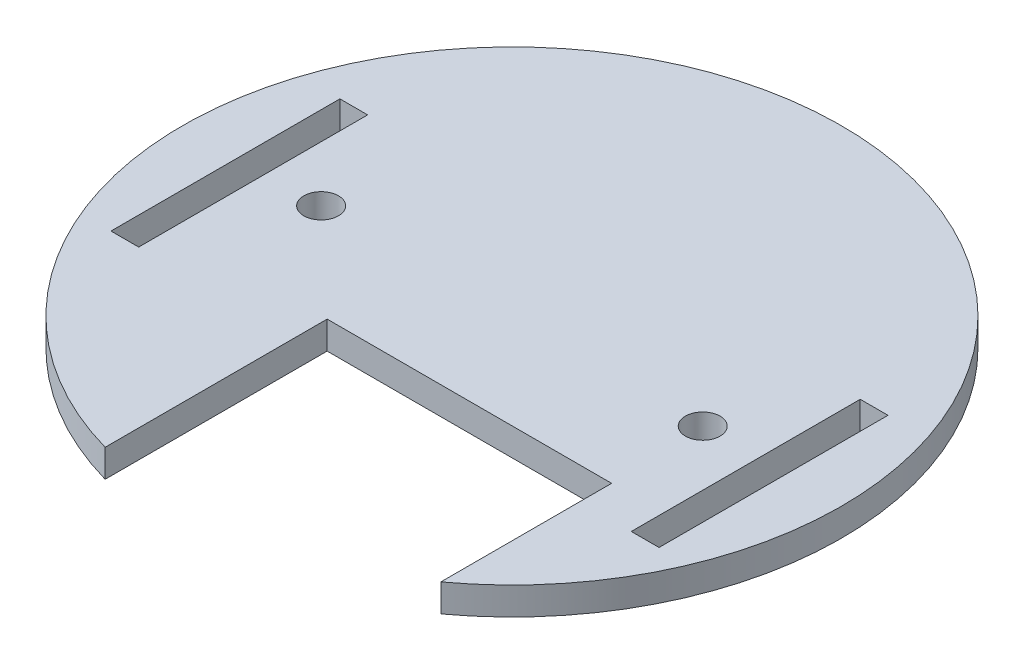
SolidWorks part; units mm, degrees
ref_plane "Front Plane" through (0, 0, 0) normal (0, 0, 1) x (1, 0, 0)
ref_plane "Top Plane" through (0, 0, 0) normal (0, 1, 0) x (1, 0, 0)
ref_plane "Right Plane" through (0, 0, 0) normal (1, 0, 0) x (0, 0, -1)
sketch "Sketch1" plane through (0, 0, 0) normal (0, 1, 0) x (1, 0, 0)
  line L0 (-47.5, 0) -> (47.5, 0) construction
  line L1 (0, 47.5) -> (0, -47.75) construction
  line L2 (-12.929, -45.7066) -> (-12.929, -13.7066)
  line L3 (-12.929, -13.7066) -> (28.071, -13.7066)
  line L4 (28.071, -13.7066) -> (28.071, -38.318)
  line L5 (35.5, -18.2987) -> (39.5, -18.2987)
  line L6 (-35.5, -18.2987) -> (-39.5, -18.2987)
  line L7 (-35.5, -18.2987) -> (-35.5, 9.1514)
  line L8 (-35.5, 9.1514) -> (-35.5, 14.7013)
  line L9 (-39.5, -18.2987) -> (-39.5, 14.7013)
  line L10 (35.5, 9.1514) -> (35.5, 14.7013)
  line L11 (39.5, -18.2987) -> (39.5, 14.7013)
  line L12 (35.5, -18.2987) -> (35.5, 9.1514)
  line L13 (35.5, 14.7013) -> (39.5, 14.7013)
  line L14 (-39.5, 14.7013) -> (-35.5, 14.7013)
  line L15 (-12.929, -42.8825) -> (-12.929, 45.7066) construction
  arc A0 (28.071, -38.318) -> (-12.929, -45.7066) centre (0, 0) ccw
  circle A1 centre (-27.5, 0) radius 2.5
  circle A2 centre (27.5, 0) radius 2.5
  dimension "D1" = 95
  dimension "D2" = 5
  dimension "D3" = 55
  dimension "D4" = 32
  dimension "D5" = 41
  dimension "D7" = 4
  dimension "D11" = 33
extrude "Boss-Extrude2" add sketch "Sketch1" along normal blind 4
